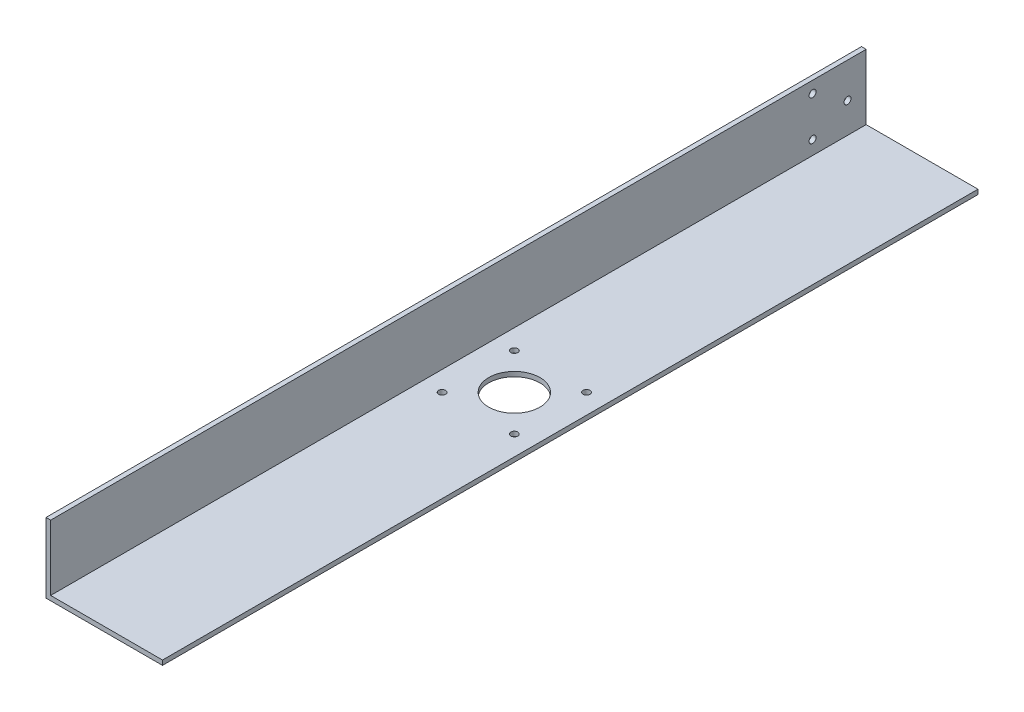
SolidWorks part; units mm, degrees
ref_plane "Front Plane" through (0, 0, 0) normal (0, 0, 1) x (1, 0, 0)
ref_plane "Top Plane" through (0, 0, 0) normal (0, 1, 0) x (1, 0, 0)
ref_plane "Right Plane" through (0, 0, 0) normal (1, 0, 0) x (0, 0, -1)
sketch "Sketch1" plane through (0, 0, 0) normal (0, 0, 1) x (1, 0, 0)
  line L0 (0, 0) -> (0, 30)
  line L1 (0, 30) -> (2, 30)
  line L2 (2, 30) -> (2, 2)
  line L3 (2, 2) -> (50, 2)
  line L4 (50, 2) -> (50, 0)
  line L5 (50, 0) -> (0, 0)
extrude "Boss-Extrude1" add sketch "Sketch1" along normal up to surface (350 mm away)
sketch "Sketch7" plane through (0, 2, 0) normal (0, 1, 0) x (1, 0, 0)
  circle A0 centre (26, -175) radius 11
  point P7 (2, -350)
extrude "Cut-Extrude1" cut sketch "Sketch7" against normal through all from surface at 0 starting at face at (26, 2, 175)
sketch "Sketch8" plane through (0, 2, 0) normal (0, 1, 0) x (1, 0, 0)
  circle A0 centre (41.5, -190.5) radius 1.5
  circle A1 centre (41.5, -159.5) radius 1.5
  circle A2 centre (10.5, -190.5) radius 1.5
  circle A3 centre (10.5, -159.5) radius 1.5
extrude "Cut-Extrude2" cut sketch "Sketch8" against normal through all
hole_wizard "Ø3.0 (3) Diameter Hole1" positions "Sketch9" profile "Sketch10" hole size "Ø3.0" standard "ISO"
sketch "Sketch9" plane through (0, 182.32, 128.862) normal (-1, 0, 0) x (0, 0, -1)
  point P0 (105.862, 174.32)
  point P2 (105.862, 157.32)
  point P4 (120.862, 167.32)
sketch "Sketch10" plane through (0, 8, 23) normal (0, 1, 0) x (0, 0, 1)
  line L0 (0, 0) -> (0, 1.999)
  line L1 (0, 1.999) -> (1.5, 1.999)
  line L2 (1.5, 1.999) -> (1.5, 0)
  line L3 (1.5, 0) -> (0, 0)
  line L4 (0, -6.35) -> (0, 107.95) construction
  dimension "Thru Hole Dia." = 3
  dimension "Thru Hole Depth" = 1.999
